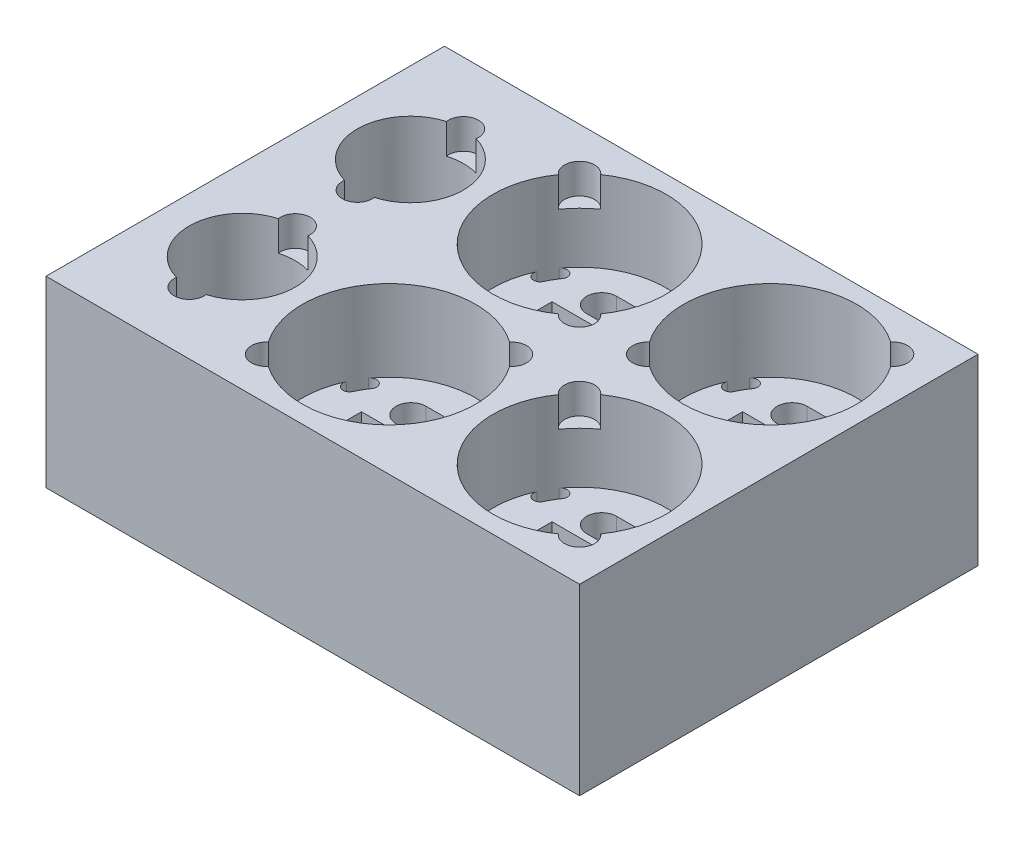
SolidWorks part; units mm, degrees
ref_plane "Спереди" through (0, 0, 0) normal (0, 0, 1) x (1, 0, 0)
ref_plane "Сверху" through (0, 0, 0) normal (0, 1, 0) x (1, 0, 0)
ref_plane "Справа" through (0, 0, 0) normal (1, 0, 0) x (0, 0, -1)
sketch "Эскиз1" plane through (0, 0, 0) normal (0, 1, 0) x (1, 0, 0)
  line L1 (0, 398) -> (533, 398)
  line L2 (0, 398) -> (0, 0)
  line L3 (0, 0) -> (533, 0)
  line L4 (533, 398) -> (533, 0)
  dimension "D1" = 533
  dimension "D2" = 398
extrude "Наполнитель" add sketch "Эскиз1" against normal blind 183
sketch "Эскиз2" plane through (0, 0, 0) normal (0, 1, 0) x (1, 0, 0)
  line L0 (429.1667, 380.6667) -> (429.1667, 398) construction
  line L1 (533, 398) -> (0, 398) construction
  line L2 (429.1667, 17.3333) -> (429.1667, 0) construction
  line L3 (0, 0) -> (533, 0) construction
  line L4 (515.6667, 294.1667) -> (533, 294.1667) construction
  line L5 (533, 0) -> (533, 398) construction
  line L6 (515.6667, 103.8333) -> (533, 103.8333) construction
  line L7 (238.8333, 207.6667) -> (238.8333, 190.3333) construction
  line L8 (325.3333, 294.1667) -> (342.6667, 294.1667) construction
  line L9 (325.3333, 103.8333) -> (342.6667, 103.8333) construction
  line L10 (429.1667, 207.6667) -> (429.1667, 190.3333) construction
  circle A0 centre (429.1667, 103.8333) radius 86.5
  circle A1 centre (238.8333, 103.8333) radius 86.5
  circle A2 centre (238.8333, 294.1667) radius 86.5
  circle A3 centre (429.1667, 294.1667) radius 86.5
  dimension "D1" = 173
  dimension "D2" = 2
  dimension "D3" = 2
extrude "Р597" cut sketch "Эскиз2" against normal blind 81
sketch "Эскиз3" plane through (0, 0, 0) normal (0, 1, 0) x (1, 0, 0)
  line L0 (81, 336) -> (81, 398) construction
  line L1 (533, 398) -> (0, 398) construction
  line L2 (28, 283) -> (0, 283) construction
  line L3 (0, 398) -> (0, 0) construction
  line L4 (81, 62) -> (81, 0) construction
  line L5 (0, 0) -> (533, 0) construction
  line L6 (28, 115) -> (0, 115) construction
  line L7 (81, 230) -> (81, 168) construction
  circle A0 centre (81, 283) radius 53
  circle A1 centre (81, 115) radius 53
  dimension "D2" = 106
  dimension "D4" = 28
  dimension "D1" = 2
extrude "КМЕ-101" cut sketch "Эскиз3" against normal blind 150
sketch "Эскиз4" plane through (0, 0, 0) normal (0, 1, 0) x (1, 0, 0)
  line L0 (81, 336) -> (81, 230) construction
  line L1 (81, 168) -> (81, 62) construction
  line L2 (238.8333, 294.1667) -> (429.1667, 103.8333) construction
  line L6 (429.1667, 294.1667) -> (238.8333, 103.8333) construction
  line L11 (214.2639, 269.5973) -> (263.4027, 318.7361) construction
  line L16 (81, 230) -> (81, 168) construction
  circle A0 centre (81, 336) radius 15
  circle A1 centre (81, 283) radius 53 construction
  circle A2 centre (81, 283) radius 53 construction
  circle A3 centre (81, 230) radius 15
  circle A4 centre (81, 168) radius 15
  circle A5 centre (81, 115) radius 53 construction
  circle A6 centre (81, 115) radius 53 construction
  circle A7 centre (81, 62) radius 15
  circle A8 centre (299.9981, 233.0019) radius 15
  circle A9 centre (238.8333, 294.1667) radius 86.5 construction
  circle A10 centre (177.6686, 355.3314) radius 15
  circle A11 centre (368.0019, 233.0019) radius 15
  circle A12 centre (490.3314, 355.3314) radius 15
  circle A13 centre (368.0019, 164.9981) radius 15
  circle A14 centre (490.3314, 42.6686) radius 15
  circle A15 centre (299.9981, 164.9981) radius 15
  circle A16 centre (177.6686, 42.6686) radius 15
  circle A18 centre (238.8333, 103.8333) radius 86.5 construction
  circle A19 centre (429.1667, 103.8333) radius 86.5 construction
  point P32 (334, 199)
  point P34 (334, 199)
  point P49 (334, 199)
  dimension "D1" = 30
  dimension "D2" = 106
  dimension "D3" = 4
extrude "Хват" cut sketch "Эскиз4" against normal blind 30
sketch "Эскиз5" plane through (0, -81, 0) normal (0, 1, 0) x (1, 0, 0)
  line L0 (238.8333, 380.6667) -> (238.8333, 207.6667) construction
  line L1 (152.3333, 294.1667) -> (325.3333, 294.1667) construction
  line L2 (384.1667, 276.6667) -> (384.1667, 311.6667)
  line L3 (193.8333, 276.6667) -> (283.8333, 276.6667)
  line L4 (193.8333, 276.6667) -> (193.8333, 311.6667)
  line L5 (193.8333, 311.6667) -> (283.8333, 311.6667)
  line L6 (283.8333, 276.6667) -> (283.8333, 311.6667)
  line L7 (193.8333, 276.6667) -> (283.8333, 311.6667) construction
  line L8 (193.8333, 311.6667) -> (283.8333, 276.6667) construction
  line L9 (384.1667, 276.6667) -> (474.1667, 276.6667)
  line L10 (474.1667, 276.6667) -> (474.1667, 311.6667)
  line L11 (384.1667, 311.6667) -> (474.1667, 311.6667)
  line L12 (384.1667, 86.3333) -> (384.1667, 121.3333)
  line L13 (384.1667, 86.3333) -> (474.1667, 86.3333)
  line L14 (474.1667, 86.3333) -> (474.1667, 121.3333)
  line L15 (384.1667, 121.3333) -> (474.1667, 121.3333)
  line L16 (193.8333, 86.3333) -> (193.8333, 121.3333)
  line L17 (193.8333, 86.3333) -> (283.8333, 86.3333)
  line L18 (283.8333, 86.3333) -> (283.8333, 121.3333)
  line L19 (193.8333, 121.3333) -> (283.8333, 121.3333)
  line L20 (429.1667, 190.3333) -> (429.1667, 17.3333) construction
  line L21 (515.6667, 103.8333) -> (342.6667, 103.8333) construction
  circle A0 centre (238.8333, 294.1667) radius 86.5 construction
  circle A1 centre (238.8333, 294.1667) radius 86.5 construction
  circle A2 centre (429.1667, 103.8333) radius 86.5 construction
  circle A3 centre (429.1667, 103.8333) radius 86.5 construction
  point P9 (238.8333, 294.1667)
  point P33 (429.1667, 121.3333)
  point P34 (429.1667, 86.3333)
  point P37 (474.1667, 103.8333)
  dimension "D1" = 90
  dimension "D2" = 35
  dimension "D3" = 2
  dimension "D4" = 2
extrude "Ложемент для запчастей" cut sketch "Эскиз5" against normal blind 30
sketch "Эскиз6" plane through (0, -81, 0) normal (0, 1, 0) x (1, 0, 0)
  line L0 (163.9221, 337.4167) -> (313.7445, 250.9167) construction
  line L1 (313.7445, 337.4167) -> (163.9221, 250.9167) construction
  line L2 (238.8333, 380.6667) -> (238.8333, 207.6667) construction
  line L3 (354.2555, 337.4167) -> (504.0779, 250.9167) construction
  line L4 (221.3333, 333.6667) -> (256.3333, 333.6667) construction
  line L5 (221.3333, 348.6667) -> (256.3333, 348.6667)
  line L6 (221.3333, 318.6667) -> (256.3333, 318.6667)
  line L7 (504.0779, 337.4167) -> (354.2555, 250.9167) construction
  line L8 (429.1667, 380.6667) -> (429.1667, 207.6667) construction
  line L9 (411.6667, 333.6667) -> (446.6667, 333.6667) construction
  line L10 (411.6667, 348.6667) -> (446.6667, 348.6667)
  line L11 (411.6667, 318.6667) -> (446.6667, 318.6667)
  line L12 (354.2555, 147.0833) -> (504.0779, 60.5833) construction
  line L13 (504.0779, 147.0833) -> (354.2555, 60.5833) construction
  line L14 (429.1667, 190.3333) -> (429.1667, 17.3333) construction
  line L15 (411.6667, 143.3333) -> (446.6667, 143.3333) construction
  line L16 (411.6667, 158.3333) -> (446.6667, 158.3333)
  line L17 (411.6667, 128.3333) -> (446.6667, 128.3333)
  line L18 (163.9221, 147.0833) -> (313.7445, 60.5833) construction
  line L19 (313.7445, 147.0833) -> (163.9221, 60.5833) construction
  line L20 (238.8333, 190.3333) -> (238.8333, 17.3333) construction
  line L21 (221.3333, 143.3333) -> (256.3333, 143.3333) construction
  line L22 (221.3333, 158.3333) -> (256.3333, 158.3333)
  line L23 (221.3333, 128.3333) -> (256.3333, 128.3333)
  circle A0 centre (238.8333, 294.1667) radius 86.5 construction
  circle A1 centre (238.8333, 294.1667) radius 86.5 construction
  arc A5 (221.3333, 348.6667) -> (221.3333, 318.6667) centre (221.3333, 333.6667) ccw
  arc A6 (256.3333, 318.6667) -> (256.3333, 348.6667) centre (256.3333, 333.6667) ccw
  arc A22 (304.0602, 340.4857) -> (311.5602, 327.4953) centre (238.8333, 294.1667) cw construction
  arc A23 (317.4693, 330.2033) -> (309.3599, 344.2491) centre (238.8333, 294.1667) ccw
  arc A24 (305.6512, 324.7874) -> (298.7605, 336.7223) centre (238.8333, 294.1667) ccw
  arc A25 (305.6512, 324.7874) -> (317.4693, 330.2033) centre (311.5602, 327.4953) ccw
  arc A26 (166.1064, 327.4953) -> (173.6064, 340.4857) centre (238.8333, 294.1667) cw construction
  arc A27 (168.3067, 344.2491) -> (160.1974, 330.2033) centre (238.8333, 294.1667) ccw
  arc A28 (178.9061, 336.7223) -> (172.0155, 324.7874) centre (238.8333, 294.1667) ccw
  arc A29 (178.9061, 336.7223) -> (168.3067, 344.2491) centre (173.6064, 340.4857) ccw
  arc A30 (160.1974, 330.2033) -> (172.0155, 324.7874) centre (166.1064, 327.4953) ccw
  arc A31 (309.3599, 344.2491) -> (298.7605, 336.7223) centre (304.0602, 340.4857) ccw
  arc A32 (246.3333, 214.519) -> (231.3333, 214.519) centre (238.8333, 294.1667) cw construction
  arc A33 (230.724, 208.0476) -> (246.9427, 208.0476) centre (238.8333, 294.1667) ccw
  arc A34 (231.9427, 220.9904) -> (245.724, 220.9904) centre (238.8333, 294.1667) ccw
  arc A35 (231.9427, 220.9904) -> (230.724, 208.0476) centre (231.3333, 214.519) ccw
  arc A36 (246.9427, 208.0476) -> (245.724, 220.9904) centre (246.3333, 214.519) ccw
  arc A37 (411.6667, 348.6667) -> (411.6667, 318.6667) centre (411.6667, 333.6667) ccw
  arc A38 (446.6667, 318.6667) -> (446.6667, 348.6667) centre (446.6667, 333.6667) ccw
  arc A39 (356.4398, 327.4953) -> (363.9398, 340.4857) centre (429.1667, 294.1667) cw construction
  arc A40 (358.6401, 344.2491) -> (350.5307, 330.2033) centre (429.1667, 294.1667) ccw
  arc A41 (369.2395, 336.7223) -> (362.3488, 324.7874) centre (429.1667, 294.1667) ccw
  arc A42 (369.2395, 336.7223) -> (358.6401, 344.2491) centre (363.9398, 340.4857) ccw
  arc A43 (350.5307, 330.2033) -> (362.3488, 324.7874) centre (356.4398, 327.4953) ccw
  arc A44 (494.3936, 340.4857) -> (501.8936, 327.4953) centre (429.1667, 294.1667) cw construction
  arc A45 (507.8026, 330.2033) -> (499.6933, 344.2491) centre (429.1667, 294.1667) ccw
  arc A46 (495.9845, 324.7874) -> (489.0939, 336.7223) centre (429.1667, 294.1667) ccw
  arc A47 (495.9845, 324.7874) -> (507.8026, 330.2033) centre (501.8936, 327.4953) ccw
  arc A48 (499.6933, 344.2491) -> (489.0939, 336.7223) centre (494.3936, 340.4857) ccw
  arc A49 (436.6667, 214.519) -> (421.6667, 214.519) centre (429.1667, 294.1667) cw construction
  arc A50 (421.0573, 208.0476) -> (437.276, 208.0476) centre (429.1667, 294.1667) ccw
  arc A51 (422.276, 220.9904) -> (436.0573, 220.9904) centre (429.1667, 294.1667) ccw
  arc A52 (422.276, 220.9904) -> (421.0573, 208.0476) centre (421.6667, 214.519) ccw
  arc A53 (437.276, 208.0476) -> (436.0573, 220.9904) centre (436.6667, 214.519) ccw
  arc A54 (411.6667, 158.3333) -> (411.6667, 128.3333) centre (411.6667, 143.3333) ccw
  arc A55 (446.6667, 128.3333) -> (446.6667, 158.3333) centre (446.6667, 143.3333) ccw
  arc A56 (356.4398, 137.162) -> (363.9398, 150.1524) centre (429.1667, 103.8333) cw construction
  arc A57 (358.6401, 153.9158) -> (350.5307, 139.8699) centre (429.1667, 103.8333) ccw
  arc A58 (369.2395, 146.3889) -> (362.3488, 134.454) centre (429.1667, 103.8333) ccw
  arc A59 (369.2395, 146.3889) -> (358.6401, 153.9158) centre (363.9398, 150.1524) ccw
  arc A60 (350.5307, 139.8699) -> (362.3488, 134.454) centre (356.4398, 137.162) ccw
  arc A61 (494.3936, 150.1524) -> (501.8936, 137.162) centre (429.1667, 103.8333) cw construction
  arc A62 (507.8026, 139.8699) -> (499.6933, 153.9158) centre (429.1667, 103.8333) ccw
  arc A63 (495.9845, 134.454) -> (489.0939, 146.3889) centre (429.1667, 103.8333) ccw
  arc A64 (495.9845, 134.454) -> (507.8026, 139.8699) centre (501.8936, 137.162) ccw
  arc A65 (499.6933, 153.9158) -> (489.0939, 146.3889) centre (494.3936, 150.1524) ccw
  arc A66 (436.6667, 24.1857) -> (421.6667, 24.1857) centre (429.1667, 103.8333) cw construction
  arc A67 (421.0573, 17.7143) -> (437.276, 17.7143) centre (429.1667, 103.8333) ccw
  arc A68 (422.276, 30.657) -> (436.0573, 30.657) centre (429.1667, 103.8333) ccw
  arc A69 (422.276, 30.657) -> (421.0573, 17.7143) centre (421.6667, 24.1857) ccw
  arc A70 (437.276, 17.7143) -> (436.0573, 30.657) centre (436.6667, 24.1857) ccw
  arc A71 (221.3333, 158.3333) -> (221.3333, 128.3333) centre (221.3333, 143.3333) ccw
  arc A72 (256.3333, 128.3333) -> (256.3333, 158.3333) centre (256.3333, 143.3333) ccw
  arc A73 (166.1064, 137.162) -> (173.6064, 150.1524) centre (238.8333, 103.8333) cw construction
  arc A74 (168.3067, 153.9158) -> (160.1974, 139.8699) centre (238.8333, 103.8333) ccw
  arc A75 (178.9061, 146.3889) -> (172.0155, 134.454) centre (238.8333, 103.8333) ccw
  arc A76 (178.9061, 146.3889) -> (168.3067, 153.9158) centre (173.6064, 150.1524) ccw
  arc A77 (160.1974, 139.8699) -> (172.0155, 134.454) centre (166.1064, 137.162) ccw
  arc A78 (304.0602, 150.1524) -> (311.5602, 137.162) centre (238.8333, 103.8333) cw construction
  arc A79 (317.4693, 139.8699) -> (309.3599, 153.9158) centre (238.8333, 103.8333) ccw
  arc A80 (305.6512, 134.454) -> (298.7605, 146.3889) centre (238.8333, 103.8333) ccw
  arc A81 (305.6512, 134.454) -> (317.4693, 139.8699) centre (311.5602, 137.162) ccw
  arc A82 (309.3599, 153.9158) -> (298.7605, 146.3889) centre (304.0602, 150.1524) ccw
  arc A83 (246.3333, 24.1857) -> (231.3333, 24.1857) centre (238.8333, 103.8333) cw construction
  arc A84 (230.724, 17.7143) -> (246.9427, 17.7143) centre (238.8333, 103.8333) ccw
  arc A85 (231.9427, 30.657) -> (245.724, 30.657) centre (238.8333, 103.8333) ccw
  arc A86 (231.9427, 30.657) -> (230.724, 17.7143) centre (231.3333, 24.1857) ccw
  arc A87 (246.9427, 17.7143) -> (245.724, 30.657) centre (246.3333, 24.1857) ccw
  circle A88 centre (429.1667, 103.8333) radius 86.5 construction
  circle A89 centre (429.1667, 294.1667) radius 86.5 construction
  point P6 (238.8333, 294.1667)
  point P7 (238.8333, 294.1667)
  point P12 (238.8333, 294.1667)
  point P19 (169.5513, 334.1667)
  point P20 (308.1154, 334.1667)
  point P24 (238.8333, 333.6667)
  point P35 (238.8333, 214.1667)
  point P41 (238.8333, 294.1667)
  point P48 (429.1667, 294.1667)
  point P53 (359.8846, 334.1667)
  point P54 (498.4487, 334.1667)
  point P58 (429.1667, 333.6667)
  point P69 (429.1667, 214.1667)
  point P75 (429.1667, 294.1667)
  point P89 (429.1667, 103.8333)
  point P97 (359.8846, 143.8333)
  point P98 (498.4487, 143.8333)
  point P102 (429.1667, 143.3333)
  point P113 (429.1667, 23.8333)
  point P119 (429.1667, 103.8333)
  point P131 (238.8333, 103.8333)
  point P136 (169.5513, 143.8333)
  point P137 (308.1154, 143.8333)
  point P141 (238.8333, 143.3333)
  point P152 (238.8333, 23.8333)
  point P158 (238.8333, 103.8333)
  dimension "D6" = 6.5
  dimension "D1" = 120
  dimension "D2" = 120
  dimension "D4" = 35
  dimension "D5" = 30
  dimension "D7" = 6.5
  dimension "D8" = 47
  dimension "D9" = 3
  dimension "D13" = 15
  dimension "D10" = 2
  dimension "D11" = 2
extrude "Вырез ножек Р597" cut sketch "Эскиз6" against normal blind 30
